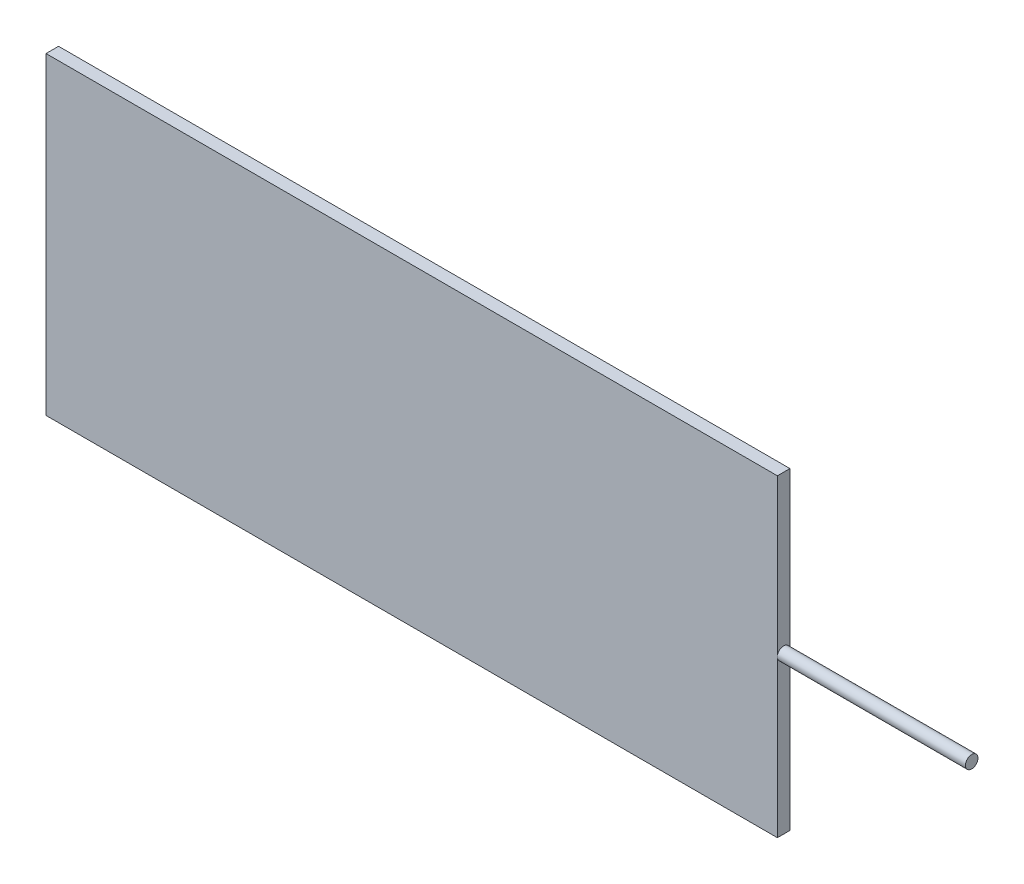
SolidWorks part; units mm, degrees
ref_plane "前视基准面" through (0, 0, 0) normal (0, 0, 1) x (1, 0, 0)
ref_plane "上视基准面" through (0, 0, 0) normal (0, 1, 0) x (1, 0, 0)
ref_plane "右视基准面" through (0, 0, 0) normal (1, 0, 0) x (0, 0, -1)
sketch "草图1" plane through (0, 0, 0) normal (0, 0, 1) x (1, 0, 0)
  line L1 (0, 0) -> (350, 0)
  line L2 (0, 0) -> (0, 150)
  line L3 (0, 150) -> (350, 150)
  line L4 (350, 0) -> (350, 150)
  dimension "D1" = 150
  dimension "D2" = 350
extrude "凸台-拉伸1" add sketch "草图1" along normal blind 6
sketch "草图2" plane through (350, 0, 0) normal (1, 0, 0) x (0, 0, -1)
  line L0 (-6, 75) -> (0, 75) construction
  line L1 (-6, 0) -> (-6, 150) construction
  line L2 (0, 0) -> (0, 150) construction
  circle A0 centre (-3, 75) radius 3
extrude "凸台-拉伸2" add sketch "草图2" along normal blind 90
